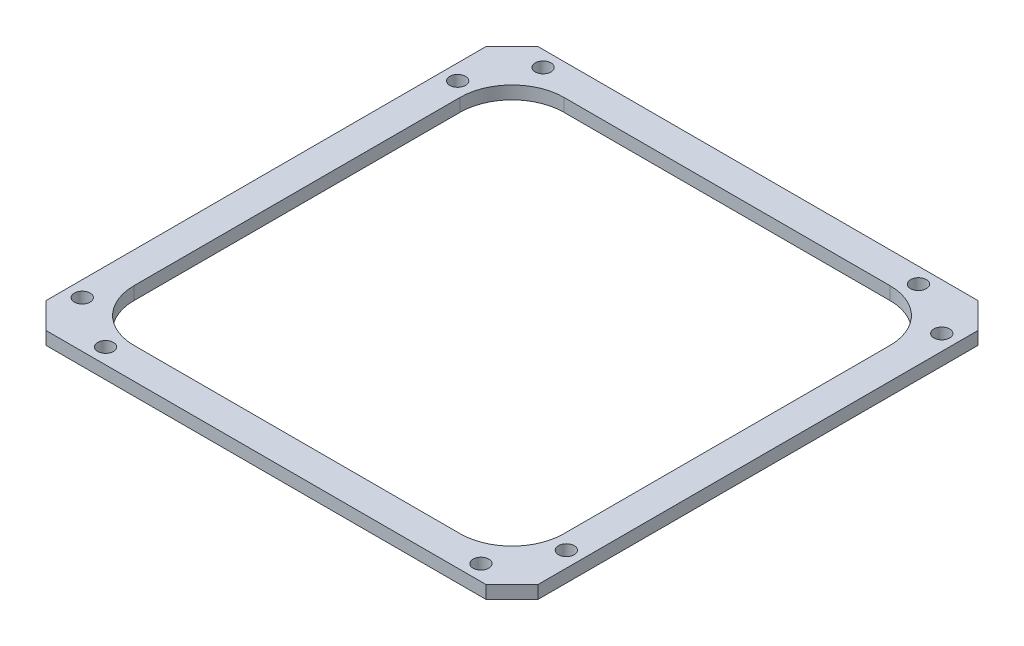
SolidWorks part; units mm, degrees
ref_plane "Front Plane" through (0, 0, 0) normal (0, 0, 1) x (1, 0, 0)
ref_plane "Top Plane" through (0, 0, 0) normal (0, 1, 0) x (1, 0, 0)
ref_plane "Right Plane" through (0, 0, 0) normal (1, 0, 0) x (0, 0, -1)
sketch "Sketch1" plane through (0, 0, 0) normal (0, 1, 0) x (1, 0, 0)
  line L1 (-95, 95) -> (95, 95)
  line L2 (-95, 95) -> (-95, -95)
  line L3 (-95, -95) -> (95, -95)
  line L4 (95, 95) -> (95, -95)
  line L5 (-95, 95) -> (95, -95) construction
  line L6 (-95, -95) -> (95, 95) construction
  point P0 (0, 0)
  dimension "182" = 190
  dimension "D2" = 190
extrude "Boss-Extrude1" add sketch "Sketch1" along normal blind 5 contours L2 L3 L4 L1
sketch "Sketch2" plane through (0, 5, 0) normal (0, 1, 0) x (1, 0, 0)
  line L0 (-95, 95) -> (95, 95) construction
  line L1 (-83, 83) -> (83, 83)
  line L2 (-83, 83) -> (-83, -83)
  line L3 (-83, -83) -> (83, -83)
  line L4 (83, 83) -> (83, -83)
  line L5 (-83, 83) -> (83, -83) construction
  line L6 (-83, -83) -> (83, 83) construction
  line L7 (-95, -95) -> (95, -95) construction
  line L8 (-95, 95) -> (-95, -95) construction
  line L9 (95, 95) -> (95, -95) construction
  point P0 (0, 0)
  dimension "D1" = 12
  dimension "D2" = 12
  dimension "D3" = 12
  dimension "D4" = 12
extrude "Cut-Extrude1" cut sketch "Sketch2" against normal through all
fillet "Fillet1" radius 20 4 edges at (83, 2.5, 83) (-83, 2.5, 83) (-83, 2.5, -83) (83, 2.5, -83)
sketch "Sketch3" plane through (0, 5, 0) normal (0, 1, 0) x (1, 0, 0)
  line L0 (0, 83) -> (0, 95) construction
  line L1 (63, 83) -> (-63, 83) construction
  line L2 (-95, 95) -> (95, 95) construction
  line L3 (-95, 89) -> (95, 89) construction
  line L4 (-95, 95) -> (-95, -95) construction
  line L5 (95, 95) -> (95, -95) construction
  line L9 (95, 89) -> (-95, 89) construction
  line L12 (-95, -95) -> (95, -95) construction
  line L13 (-89, -95) -> (-89, 95) construction
  line L14 (-89, 95) -> (-89, -95) construction
  line L16 (95, -89) -> (-95, -89) construction
  line L17 (-95, -89) -> (95, -89) construction
  line L18 (89, 95) -> (89, -95) construction
  line L19 (89, -95) -> (89, 95) construction
  circle A0 centre (-77, 89) radius 3.05
  circle A1 centre (-89, 68) radius 3.05
  circle A14 centre (77, -89) radius 3.05 [skipped]
  circle A15 centre (89, -68) radius 3.05 [skipped]
  circle A16 centre (-89, -77) radius 3.05 [skipped]
  circle A17 centre (-68, -89) radius 3.05 [skipped]
  circle A18 centre (89, 77) radius 3.05 [skipped]
  circle A19 centre (68, 89) radius 3.05 [skipped]
  circle A22 centre (89, 77) radius 3.05
  circle A23 centre (68, 89) radius 3.05
  circle A26 centre (77, -89) radius 3.05
  circle A27 centre (89, -68) radius 3.05
  circle A30 centre (-89, -77) radius 3.05
  circle A31 centre (-68, -89) radius 3.05
  point P39 (-4, -4)
  point P52 (0, 0)
  point P81 (0, 0)
  dimension "D1" = 6.1
  dimension "D2" = 6.1
  dimension "D3" = 18
  dimension "D4" = 27
  dimension "D5" = 4
  dimension "D10" = 4
extrude "Cut-Extrude2" cut sketch "Sketch3" against normal through all
chamfer "Chamfer1" distance 10 angle 45 4 edges at (95, 2.5, -95) (-95, 2.5, -95) (-95, 2.5, 95) (95, 2.5, 95)
